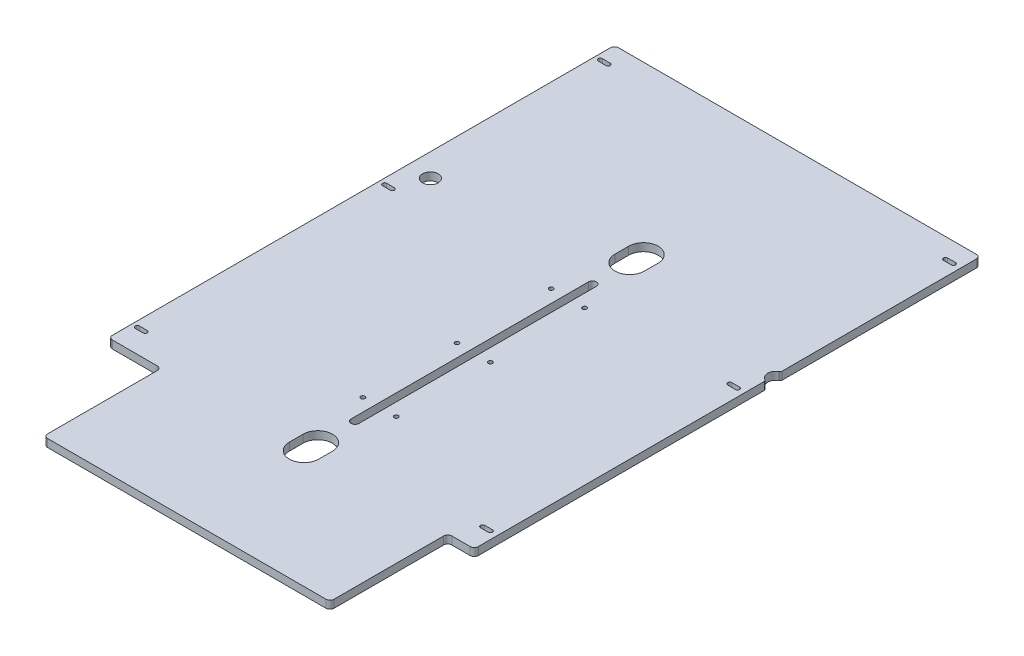
SolidWorks part; units mm, degrees
material "PE High Density"
ref_plane "Front" through (0, 0, 0) normal (0, 0, 1) x (1, 0, 0)
ref_plane "Top" through (0, 0, 0) normal (0, 1, 0) x (1, 0, 0)
ref_plane "Right" through (0, 0, 0) normal (1, 0, 0) x (0, 0, -1)
sketch "Sketch1" plane through (0, 0, 0) normal (0, 1, 0) x (1, 0, 0)
  line L0 (0, 0) -> (96.0438, 0)
  line L1 (96.0438, 0) -> (96.0438, -190.5)
  line L2 (96.0438, -190.5) -> (559.5938, -190.5)
  line L3 (559.5938, -190.5) -> (559.5938, 0)
  line L4 (559.5938, 0) -> (606.425, 0)
  line L5 (606.425, 0) -> (606.425, 819.15)
  line L6 (606.425, 819.15) -> (0, 819.15)
  line L7 (0, 819.15) -> (0, 0)
  line L8 (25.4, 0) -> (25.4, 819.15) construction
  line L9 (19.05, 38.1) -> (31.75, 38.1) construction
  line L10 (19.05, 41.4782) -> (31.75, 41.4782)
  line L11 (19.05, 34.7218) -> (31.75, 34.7218)
  line L12 (19.05, 438.15) -> (31.75, 438.15) construction
  line L13 (19.05, 441.5282) -> (31.75, 441.5282)
  line L14 (19.05, 434.7718) -> (31.75, 434.7718)
  line L15 (31.75, 787.4) -> (19.05, 787.4) construction
  line L16 (31.75, 784.0218) -> (19.05, 784.0218)
  line L17 (31.75, 790.7782) -> (19.05, 790.7782)
  line L18 (303.2125, 819.15) -> (303.2125, -190.5) construction
  line L19 (584.2, 787.4) -> (584.2, 438.15) construction
  line L20 (577.85, 787.4) -> (590.55, 787.4) construction
  line L21 (577.85, 784.0218) -> (590.55, 784.0218)
  line L22 (577.85, 790.7782) -> (590.55, 790.7782)
  line L23 (590.55, 438.15) -> (577.85, 438.15) construction
  line L24 (590.55, 441.5282) -> (577.85, 441.5282)
  line L25 (590.55, 434.7718) -> (577.85, 434.7718)
  line L26 (590.55, 38.1) -> (577.85, 38.1) construction
  line L27 (590.55, 41.4782) -> (577.85, 41.4782)
  line L28 (590.55, 34.7218) -> (577.85, 34.7218)
  line L29 (327.8187, -190.5) -> (327.8187, 819.15) construction
  line L30 (584.2, 438.15) -> (584.2, 38.1) construction
  arc A1 (19.05, 41.4782) -> (19.05, 34.7218) centre (19.05, 38.1) ccw
  arc A2 (31.75, 34.7218) -> (31.75, 41.4782) centre (31.75, 38.1) ccw
  arc A3 (19.05, 441.5282) -> (19.05, 434.7718) centre (19.05, 438.15) ccw
  arc A4 (31.75, 434.7718) -> (31.75, 441.5282) centre (31.75, 438.15) ccw
  arc A5 (31.75, 784.0218) -> (31.75, 790.7782) centre (31.75, 787.4) ccw
  arc A6 (19.05, 790.7782) -> (19.05, 784.0218) centre (19.05, 787.4) ccw
  arc A7 (577.85, 784.0218) -> (577.85, 790.7782) centre (577.85, 787.4) cw
  arc A8 (590.55, 790.7782) -> (590.55, 784.0218) centre (590.55, 787.4) cw
  arc A9 (590.55, 441.5282) -> (590.55, 434.7718) centre (590.55, 438.15) cw
  arc A10 (577.85, 434.7718) -> (577.85, 441.5282) centre (577.85, 438.15) cw
  arc A11 (590.55, 41.4782) -> (590.55, 34.7218) centre (590.55, 38.1) cw
  arc A12 (577.85, 34.7218) -> (577.85, 41.4782) centre (577.85, 38.1) cw
  point P13 (25.4, 38.1)
  point P20 (25.4, 438.15)
  point P27 (25.4, 787.4)
  point P38 (584.2, 787.4)
  point P45 (584.2, 438.15)
  point P52 (584.2, 38.1)
  dimension "D1" = 96.0438
  dimension "D2" = 46.8312
  dimension "D3" = 819.15
  dimension "D4" = 25.4
  dimension "D5" = 6.7564
  dimension "D6" = 38.1
  dimension "D7" = 12.7
  dimension "D8" = 400.05
  dimension "D9" = 349.25
  dimension "D10" = 190.5
  dimension "D11" = 463.55
  dimension "D12" = 22.225
extrude "Boss-Extrude1" add sketch "Sketch1" along normal blind 12.7
fillet "Fillet1" radius 6.604 2 edges at (96.0438, 6.35, 0) (559.5938, 6.35, 0)
fillet "Fillet2" radius 6.604 6 edges at (0, 6.35, -819.15) (606.425, 6.35, -819.15) (606.425, 6.35, 0) (559.5938, 6.35, 190.5) (0, 6.35, 0) (96.0438, 6.35, 190.5)
sketch "Sketch2" plane through (0, 12.7, 0) normal (0, 1, 0) x (1, 0, 0)
  line L1 (606.425, 6.604) -> (606.425, 812.546) construction
  line L3 (577.85, 438.15) -> (590.55, 438.15) construction
  line L4 (606.425, 505.867) -> (606.425, 461.873)
  line L5 (606.425, 483.87) -> (47.625, 483.87) construction
  line L6 (0, 812.546) -> (0, 6.604) construction
  arc A3 (600.075, 494.8685) -> (600.075, 472.8715) centre (606.425, 483.87) ccw
  arc A4 (600.075, 494.8685) -> (606.425, 505.867) centre (593.725, 505.867) ccw
  arc A5 (606.425, 461.873) -> (600.075, 472.8715) centre (593.725, 461.873) ccw
  circle A6 centre (47.625, 483.87) radius 12.7
  dimension "D1" = 25.4
  dimension "D2" = 45.72
  dimension "D3" = 47.625
extrude "Cut-Extrude1" cut sketch "Sketch2" against normal through all
sketch "Sketch4" plane through (0, 0, 0) normal (0, -1, 0) x (1, 0, 0)
  line L0 (0, -812.546) -> (0, -6.604) construction
  line L3 (327.025, -527.05) -> (327.025, -549.275) construction
  line L4 (350.8375, -527.05) -> (350.8375, -549.275)
  line L5 (303.2125, -527.05) -> (303.2125, -549.275)
  line L7 (599.821, -819.15) -> (6.604, -819.15) construction
  line L8 (327.025, 0) -> (327.025, -22.225) construction
  line L9 (350.8375, 0) -> (350.8375, -22.225)
  line L10 (303.2125, 0) -> (303.2125, -22.225)
  circle A0 centre (327.025, -538.1625) radius 28.575 construction
  arc A2 (350.8375, -527.05) -> (303.2125, -527.05) centre (327.025, -527.05) ccw
  arc A3 (303.2125, -549.275) -> (350.8375, -549.275) centre (327.025, -549.275) ccw
  arc A4 (350.8375, 0) -> (303.2125, 0) centre (327.025, 0) ccw
  arc A5 (303.2125, -22.225) -> (350.8375, -22.225) centre (327.025, -22.225) ccw
  point P8 (327.025, -11.1125)
  point P12 (327.025, -538.1625)
  dimension "D2" = 57.15
  dimension "D1" = 327.025
  dimension "D3" = 527.05
  dimension "D4" = 47.625
  dimension "D5" = 22.225
  dimension "D6" = 280.9875
extrude "Cut-Extrude3" cut sketch "Sketch4" against normal through all
sketch "Sketch5" plane through (0, 0, 0) normal (0, -1, 0) x (1, 0, 0)
  line L0 (327.025, -22.225) -> (327.025, -527.05) construction
  line L1 (327.025, -466.725) -> (327.025, -82.55) construction
  line L2 (320.675, -466.725) -> (320.675, -82.55)
  line L3 (333.375, -466.725) -> (333.375, -82.55)
  arc A0 (320.675, -466.725) -> (333.375, -466.725) centre (327.025, -466.725) ccw
  arc A1 (333.375, -82.55) -> (320.675, -82.55) centre (327.025, -82.55) ccw
  point P6 (327.025, -274.6375)
  dimension "D1" = 384.175
  dimension "D2" = 12.7
extrude "Cut-Extrude4" cut sketch "Sketch5" against normal through all
sketch "Sketch6" plane through (0, 0, 0) normal (0, -1, 0) x (1, 0, 0)
  line L0 (327.025, -82.55) -> (327.025, -466.725) construction
  line L1 (327.025, -274.6375) -> (354.0125, -274.6375) construction
  line L2 (354.0125, -122.2375) -> (354.0125, -427.0375) construction
  line L3 (300.0375, -122.2375) -> (300.0375, -427.0375) construction
  circle A0 centre (354.0125, -274.6375) radius 3.3782
  circle A1 centre (354.0125, -427.0375) radius 3.3782
  circle A2 centre (354.0125, -122.2375) radius 3.3782
  circle A3 centre (300.0375, -427.0375) radius 3.3782
  circle A4 centre (300.0375, -274.6375) radius 3.3782
  circle A5 centre (300.0375, -122.2375) radius 3.3782
  dimension "D2" = 6.7564
  dimension "D1" = 26.9875
  dimension "D3" = 152.4
extrude "Cut-Extrude5" cut sketch "Sketch6" against normal through all
sketch "Sketch7" plane through (0, 0, 0) normal (0, -1, 0) x (1, 0, 0)
  line L0 (599.821, -819.15) -> (6.604, -819.15) construction
  line L1 (6.604, 0) -> (89.4398, 0) construction
  line L2 (0, -812.546) -> (0, -6.604) construction
  line L3 (7.366, -819.15) -> (6.604, -819.15)
  line L4 (6.604, 0) -> (7.366, 0)
  line L5 (0, -812.546) -> (0, -6.604)
  line L6 (0.762, -6.604) -> (0.762, -812.546)
  line L7 (566.1978, 0) -> (599.821, 0) construction
  line L8 (606.425, -505.867) -> (606.425, -812.546) construction
  line L9 (606.425, -6.604) -> (606.425, -461.873) construction
  line L10 (566.1978, 0) -> (599.821, 0)
  line L11 (599.821, -819.15) -> (6.604, -819.15)
  line L12 (606.425, -505.867) -> (606.425, -812.546)
  line L13 (606.425, -6.604) -> (606.425, -461.873)
  line L14 (605.663, -504.5472) -> (605.663, -812.546)
  line L15 (605.663, -6.604) -> (605.663, -462.3309)
  arc A0 (0, -812.546) -> (6.604, -819.15) centre (6.604, -812.546) ccw construction
  arc A1 (6.604, 0) -> (0, -6.604) centre (6.604, -6.604) ccw construction
  arc A2 (0, -812.546) -> (6.604, -819.15) centre (6.604, -812.546) ccw
  arc A3 (6.604, 0) -> (0, -6.604) centre (6.604, -6.604) ccw
  arc A4 (7.366, 0) -> (0.762, -6.604) centre (7.366, -6.604) ccw
  arc A5 (0.762, -812.546) -> (7.366, -819.15) centre (7.366, -812.546) ccw
  arc A7 (606.425, -505.867) -> (600.075, -494.8685) centre (593.725, -505.867) ccw construction
  arc A8 (600.075, -472.8715) -> (600.075, -494.8685) centre (606.425, -483.87) ccw construction
  arc A9 (600.075, -472.8715) -> (606.425, -461.873) centre (593.725, -461.873) ccw construction
  arc A11 (599.821, -819.15) -> (606.425, -812.546) centre (599.821, -812.546) ccw
  arc A12 (606.425, -505.867) -> (600.075, -494.8685) centre (593.725, -505.867) ccw
  arc A13 (600.075, -472.8715) -> (600.075, -494.8685) centre (606.425, -483.87) ccw
  arc A14 (600.075, -472.8715) -> (606.425, -461.873) centre (593.725, -461.873) ccw
  arc A15 (606.425, -6.604) -> (599.821, 0) centre (599.821, -6.604) ccw
  arc A16 (605.663, -6.604) -> (599.059, 0) centre (599.059, -6.604) ccw
  arc A17 (599.059, -819.15) -> (605.663, -812.546) centre (599.059, -812.546) ccw
  arc A18 (605.663, -504.5472) -> (600.075, -494.8685) centre (594.487, -504.5472) ccw
  arc A19 (599.694, -473.1004) -> (605.663, -462.3309) centre (592.963, -462.3309) ccw
  dimension "D1" = 0.762
  dimension "D2" = 0.762
extrude "Cut-Extrude6" cut sketch "Sketch7" against normal through all contours A18 L14 A17 L11 A11 L12 A12 | A5 L6 A4 L4 A3 L5 A2 L3 | A19 A13 A14 L13 A15 L10 A16 L15
sketch "Sketch8" plane through (0, 12.7, 0) normal (0, 1, 0) x (1, 0, 0)
  line L0 (7.366, 0) -> (89.4398, 0) construction
  line L1 (599.059, 819.15) -> (7.366, 819.15) construction
  line L2 (0.762, 6.604) -> (0.762, 812.546) construction
  line L3 (7.366, 0) -> (16.891, 0)
  line L4 (16.891, 819.15) -> (7.366, 819.15)
  line L5 (0.762, 6.604) -> (0.762, 812.546)
  line L6 (10.287, 6.604) -> (10.287, 812.546)
  line L7 (602.488, 6.604) -> (602.488, 812.546)
  line L8 (605.663, 504.5472) -> (605.663, 812.546) construction
  line L9 (599.059, 0) -> (595.884, 0)
  line L10 (605.663, 6.604) -> (605.663, 812.546)
  line L11 (599.059, 819.15) -> (595.884, 819.15)
  arc A0 (0.762, 6.604) -> (7.366, 0) centre (7.366, 6.604) ccw construction
  arc A1 (7.366, 819.15) -> (0.762, 812.546) centre (7.366, 812.546) ccw construction
  arc A2 (0.762, 6.604) -> (7.366, 0) centre (7.366, 6.604) ccw
  arc A3 (7.366, 819.15) -> (0.762, 812.546) centre (7.366, 812.546) ccw
  arc A4 (10.287, 6.604) -> (16.891, 0) centre (16.891, 6.604) ccw
  arc A5 (16.891, 819.15) -> (10.287, 812.546) centre (16.891, 812.546) ccw
  arc A6 (599.059, 0) -> (605.663, 6.604) centre (599.059, 6.604) ccw construction
  arc A7 (599.059, 0) -> (605.663, 6.604) centre (599.059, 6.604) ccw
  arc A8 (605.663, 812.546) -> (599.059, 819.15) centre (599.059, 812.546) ccw construction
  arc A9 (605.663, 812.546) -> (599.059, 819.15) centre (599.059, 812.546) ccw
  arc A10 (602.488, 812.546) -> (595.884, 819.15) centre (595.884, 812.546) ccw
  arc A11 (595.884, 0) -> (602.488, 6.604) centre (595.884, 6.604) ccw
  dimension "D2" = 9.525
  dimension "D4" = 3.175
  dimension "D1" = 2
  dimension "D3" = 2
extrude "Cut-Extrude7" cut sketch "Sketch8" against normal through all contours A5 L4 A3 L5 A2 L3 A4 L6 | L11 A10 L7 A11 L9 A7 L10 A9
fillet "Fillet3" radius 3.175 2 edges at (602.488, 6.35, -470.7311) (602.488, 6.35, -496.7442)
